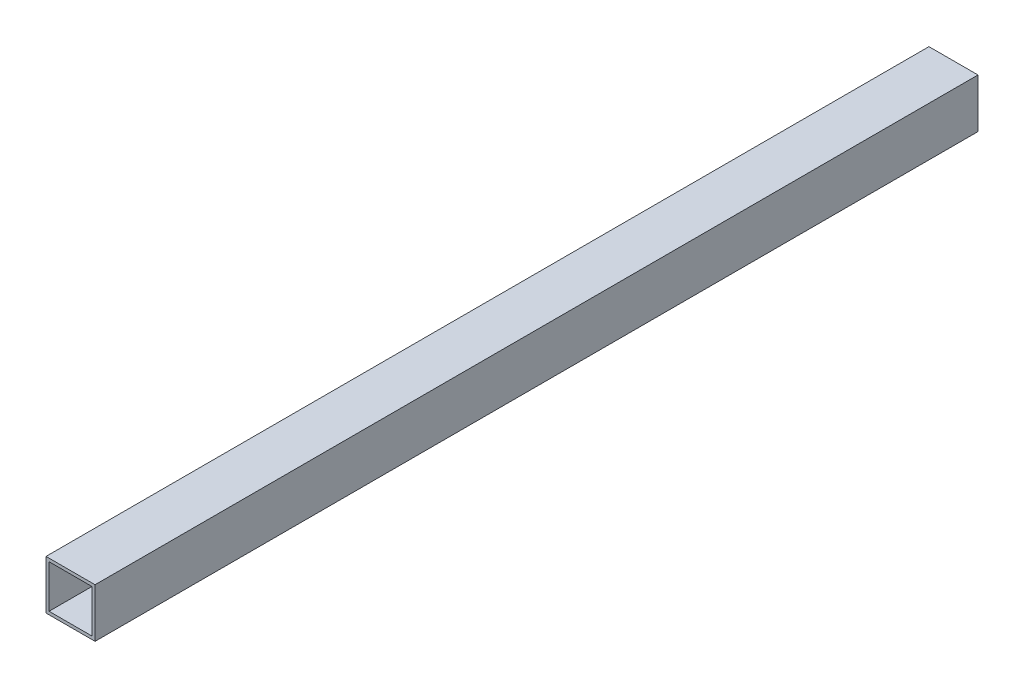
SolidWorks part; units mm, degrees
material "AISI 1020"
ref_plane "Front Plane" through (0, 0, 0) normal (0, 0, 1) x (1, 0, 0)
ref_plane "Top Plane" through (0, 0, 0) normal (0, 1, 0) x (1, 0, 0)
ref_plane "Right Plane" through (0, 0, 0) normal (1, 0, 0) x (0, 0, -1)
sketch "Sketch1" plane through (0, 0, 0) normal (0, 0, 1) x (1, 0, 0)
  line L0 (22.225, 22.225) -> (22.225, 25.4) construction
  line L1 (-25.4, -25.4) -> (25.4, -25.4)
  line L2 (-25.4, -25.4) -> (-25.4, 25.4)
  line L3 (-25.4, 25.4) -> (25.4, 25.4)
  line L4 (25.4, -25.4) -> (25.4, 25.4)
  line L5 (-25.4, -25.4) -> (25.4, 25.4) construction
  line L6 (-25.4, 25.4) -> (25.4, -25.4) construction
  line L7 (-22.225, -22.225) -> (22.225, -22.225)
  line L8 (-22.225, -22.225) -> (-22.225, 22.225)
  line L9 (-22.225, 22.225) -> (22.225, 22.225)
  line L10 (22.225, -22.225) -> (22.225, 22.225)
  line L11 (-22.225, -22.225) -> (22.225, 22.225) construction
  line L12 (-22.225, 22.225) -> (22.225, -22.225) construction
  line L13 (22.225, -22.225) -> (25.4, -22.225) construction
  point P0 (0, 0)
  point P6 (0, 0)
  dimension "D2" = 50.8
  dimension "D3" = 3.175
extrude "Boss-Extrude1" add sketch "Sketch1" along normal blind 914.4
